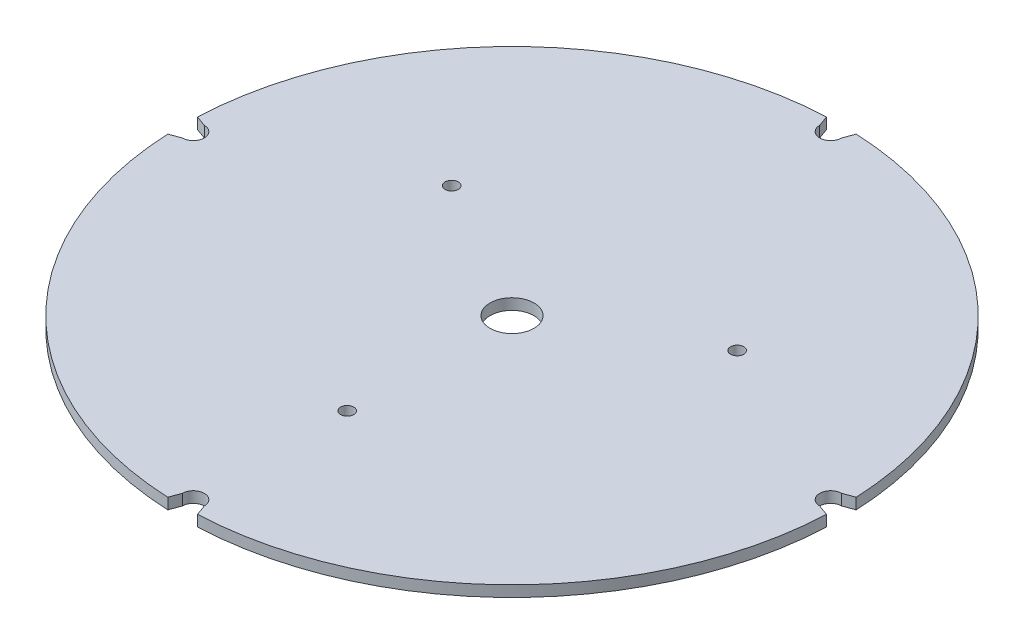
SolidWorks part; units mm, degrees
ref_plane "Front Plane" through (0, 0, 0) normal (0, 0, 1) x (1, 0, 0)
ref_plane "Top Plane" through (0, 0, 0) normal (0, 1, 0) x (1, 0, 0)
ref_plane "Right Plane" through (0, 0, 0) normal (1, 0, 0) x (0, 0, -1)
sketch "Sketch1" plane through (0, 0, 0) normal (0, 1, 0) x (1, 0, 0)
  line L0 (0, 150) -> (0, 145) construction
  line L1 (-5, 145) -> (-6.7643, 149.8474)
  line L2 (5, 145) -> (6.7643, 149.8474)
  line L3 (145, 5) -> (149.8474, 6.7643)
  line L4 (150, 0) -> (145, 0) construction
  line L5 (145, -5) -> (149.8474, -6.7643)
  line L6 (5, -145) -> (6.7643, -149.8474)
  line L7 (0, -150) -> (0, -145) construction
  line L8 (-5, -145) -> (-6.7643, -149.8474)
  line L9 (-145, -5) -> (-149.8474, -6.7643)
  line L10 (-150, 0) -> (-145, 0) construction
  line L11 (-145, 5) -> (-149.8474, 6.7643)
  circle A0 centre (0, 0) radius 150
  circle A1 centre (0, 145) radius 5
  circle A17 centre (0, 0) radius 10
  circle A24 centre (145, 0) radius 5
  circle A25 centre (0, -145) radius 5
  circle A26 centre (-145, 0) radius 5
  point P35 (0, 0)
  dimension "D1" = 300
  dimension "D2" = 10
  dimension "D6" = 20
  dimension "D3" = 5
  dimension "D4" = 20
  dimension "D5" = 4
extrude "Boss-Extrude1" add sketch "Sketch1" along normal blind 5
sketch "Sketch2" plane through (0, 5, 0) normal (0, 1, 0) x (1, 0, 0)
  line L0 (-64.9519, 37.5) -> (64.9519, 37.5) construction
  line L1 (64.9519, 37.5) -> (0, -75) construction
  line L2 (0, -75) -> (-64.9519, 37.5) construction
  circle A0 centre (0, 0) radius 75 construction
  circle A1 centre (0, -75) radius 3
  circle A2 centre (64.9519, 37.5) radius 3
  circle A3 centre (-64.9519, 37.5) radius 3
  dimension "D1" = 150
  dimension "D2" = 6
extrude "Cut-Extrude1" cut sketch "Sketch2" against normal through all both and the other way through all
